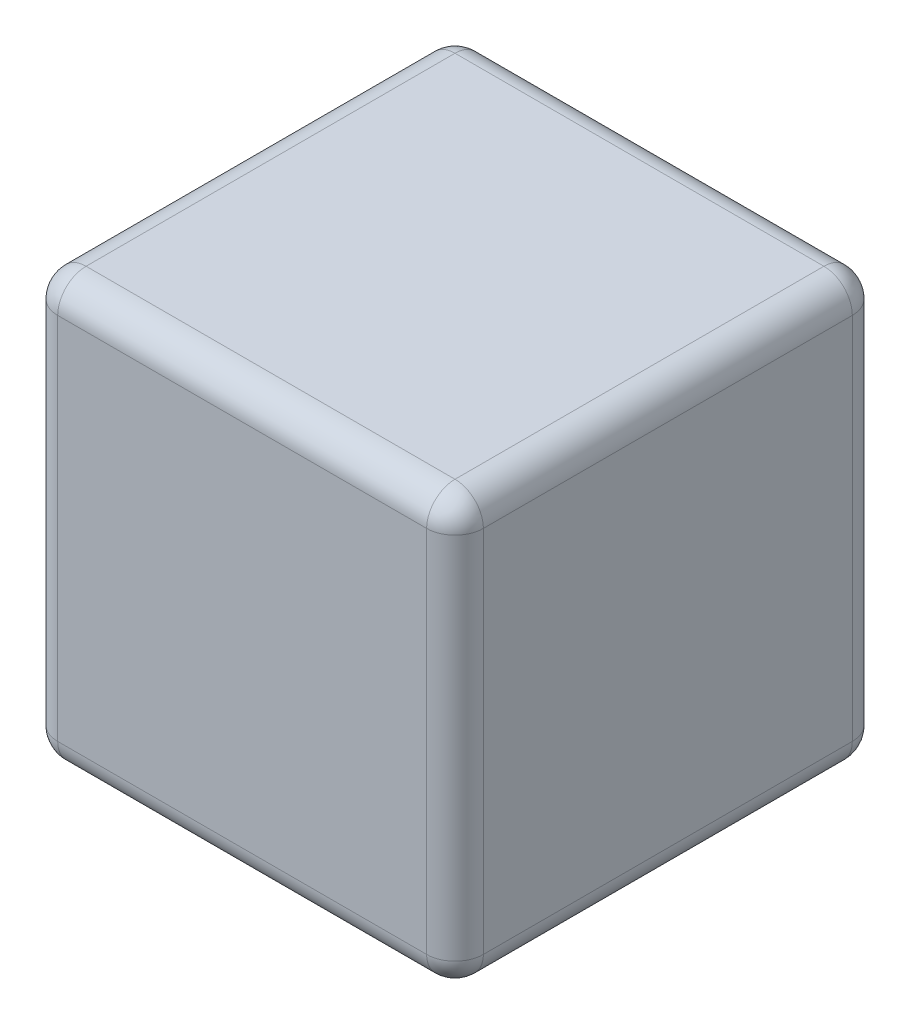
SolidWorks part; units mm, degrees
material "Pine"
ref_plane "Front Plane" through (0, 0, 0) normal (0, 0, 1) x (1, 0, 0)
ref_plane "Top Plane" through (0, 0, 0) normal (0, 1, 0) x (1, 0, 0)
ref_plane "Right Plane" through (0, 0, 0) normal (1, 0, 0) x (0, 0, -1)
other "Center of Mass"
sketch "Sketch1" plane through (0, 0, 0) normal (0, 1, 0) x (1, 0, 0)
  line L1 (-19.05, 19.05) -> (19.05, 19.05)
  line L2 (-19.05, 19.05) -> (-19.05, -19.05)
  line L3 (-19.05, -19.05) -> (19.05, -19.05)
  line L4 (19.05, 19.05) -> (19.05, -19.05)
  line L5 (-19.05, 19.05) -> (19.05, -19.05) construction
  line L6 (-19.05, -19.05) -> (19.05, 19.05) construction
  point P0 (0, 0)
  dimension "D1" = 38.1
  dimension "D2" = 38.1
extrude "Boss-Extrude1" add sketch "Sketch1" along normal blind 38.1
fillet "Fillet1" radius 2.54 12 edges at (-19.05, 0, 0) (-19.05, 19.05, -19.05) (0, 0, -19.05) (19.05, 19.05, -19.05) (19.05, 0, 0) (-19.05, 38.1, 0) (0, 38.1, -19.05) (19.05, 38.1, 0) (-19.05, 19.05, 19.05) (0, 38.1, 19.05) (19.05, 19.05, 19.05) (0, 0, 19.05)
